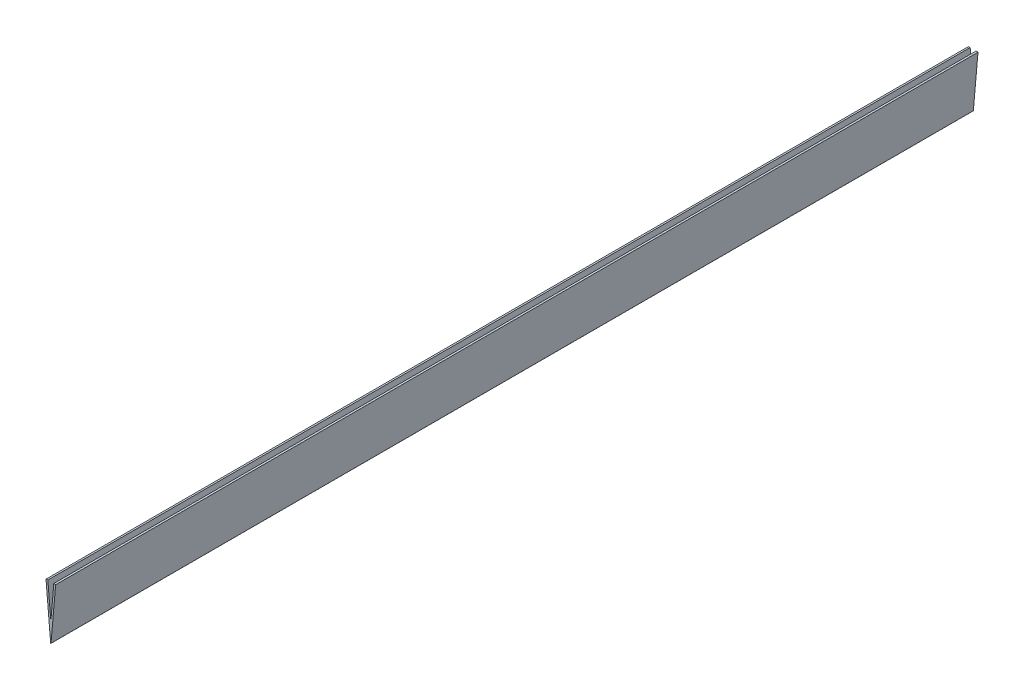
SolidWorks part; units mm, degrees
ref_plane "Front Plane" through (0, 0, 0) normal (0, 0, 1) x (1, 0, 0)
ref_plane "Top Plane" through (0, 0, 0) normal (0, 1, 0) x (1, 0, 0)
ref_plane "Right Plane" through (0, 0, 0) normal (1, 0, 0) x (0, 0, -1)
sketch "Sketch1" plane through (0, 0, 0) normal (0, 0, 1) x (1, 0, 0)
  line L0 (0, 0) -> (0.1618, 1.8499)
  line L1 (0, 0) -> (-0.1618, 1.8499)
  line L2 (-0.1618, 1.8499) -> (-0.2615, 1.8412)
  line L3 (-0.2615, 1.8412) -> (0, -1.1474)
  line L4 (0, -1.1474) -> (0.2615, 1.8412)
  line L5 (0.2615, 1.8412) -> (0.1618, 1.8499)
  line L6 (0, 0) -> (0, -1.1474) construction
  point P7 (0, -0.1401)
  dimension "D1" = 0.1
  dimension "D2" = 0.1
  dimension "D3" = 5
  dimension "D4" = 10
  dimension "D5" = 3
extrude "Boss-Extrude1" add sketch "Sketch1" along normal blind 50 contours L4 L5 L0 L1 L2 L3
fillet "Fillet1" radius 0.01 2 edges at (0, 0, 25) (0, -1.1474, 25)
